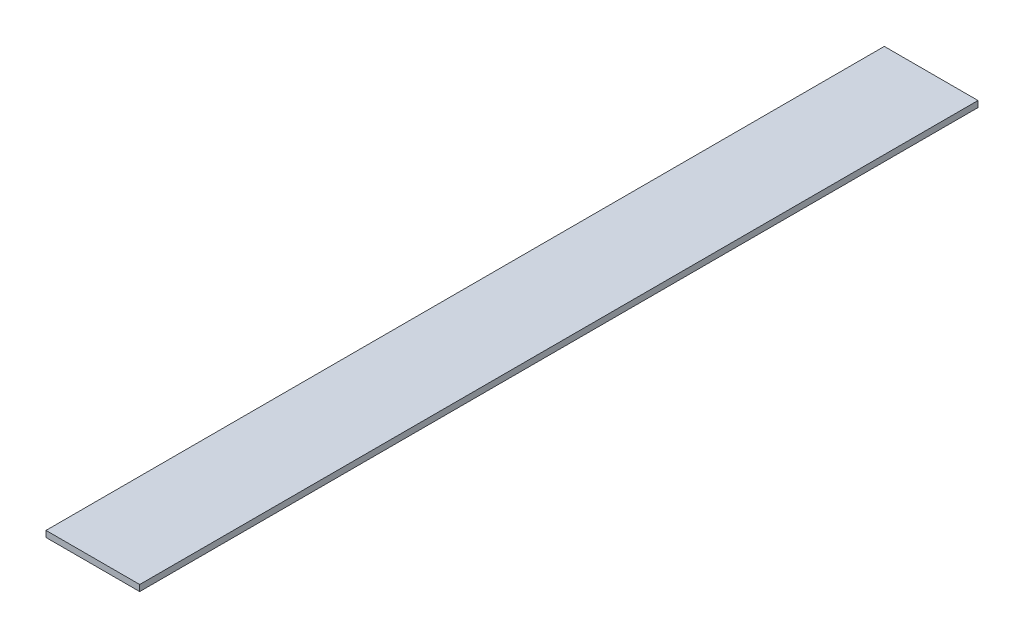
SolidWorks part; units mm, degrees
ref_plane "Front Plane" through (0, 0, 0) normal (0, 0, 1) x (1, 0, 0)
ref_plane "Top Plane" through (0, 0, 0) normal (0, 1, 0) x (1, 0, 0)
ref_plane "Right Plane" through (0, 0, 0) normal (1, 0, 0) x (0, 0, -1)
other "Configuration Table"
sketch "Sketch1" plane through (0, 0, 0) normal (0, 0, 1) x (1, 0, 0)
  line L1 (-38, 25) -> (38, 25)
  line L2 (-38, 25) -> (-38, 30)
  line L3 (-38, 30) -> (38, 30)
  line L4 (38, 25) -> (38, 30)
extrude "KAPYAG_taban_plakasi_kapali_1" add sketch "Sketch1" against normal blind 680 from offset 20 separate body
